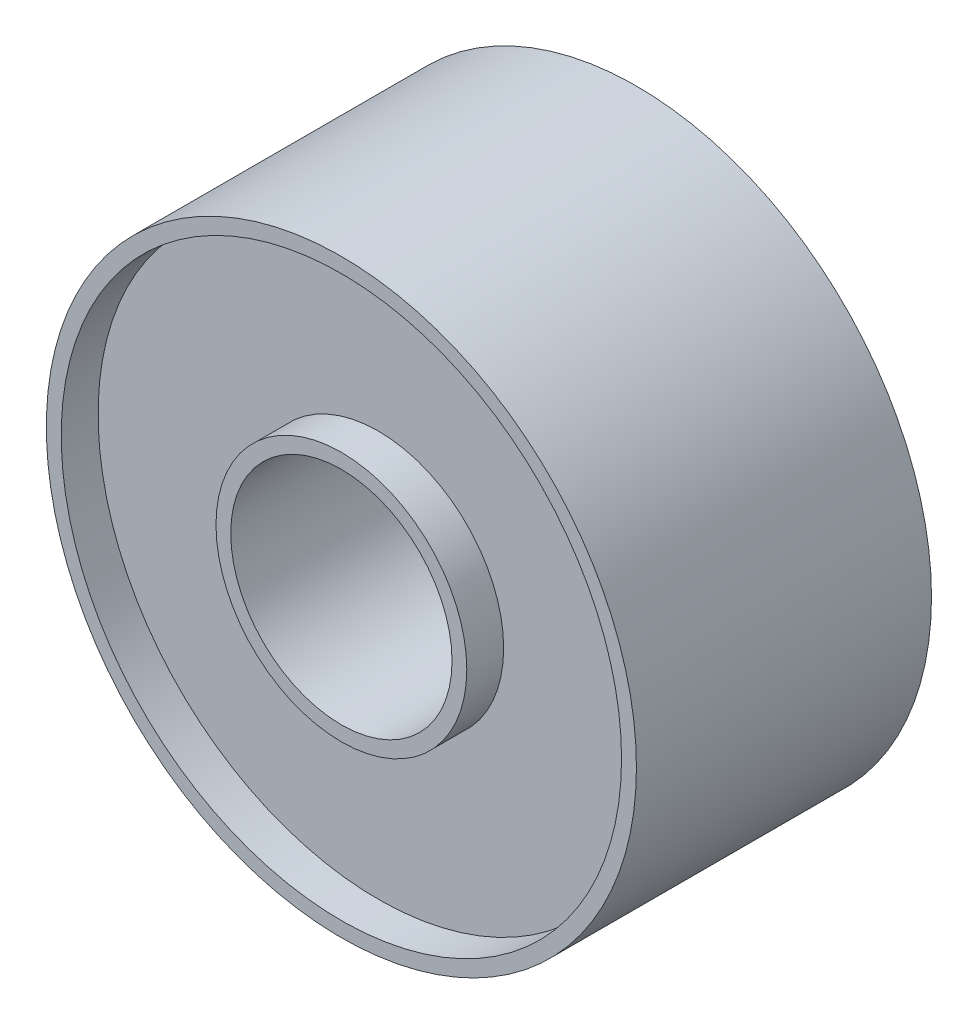
SolidWorks part; units mm, degrees
ref_plane "Front Plane" through (0, 0, 0) normal (0, 0, 1) x (1, 0, 0)
ref_plane "Top Plane" through (0, 0, 0) normal (0, 1, 0) x (1, 0, 0)
ref_plane "Right Plane" through (0, 0, 0) normal (1, 0, 0) x (0, 0, -1)
sketch "Sketch1" plane through (0, 0, 0) normal (0, 0, 1) x (1, 0, 0)
  circle A0 centre (0, 0) radius 4
  circle A1 centre (0, 0) radius 1.5
extrude "Boss-Extrude1" add sketch "Sketch1" along normal blind 4
sketch "Sketch2" plane through (0, 0, 4) normal (0, 0, 1) x (1, 0, 0)
  circle A0 centre (0, 0) radius 3.7982
  circle A1 centre (0, 0) radius 1.7
extrude "Cut-Extrude2" cut sketch "Sketch2" against normal blind 0.5
sketch "Sketch3" plane through (0, 0, 0) normal (0, 0, -1) x (-1, 0, 0)
  circle A0 centre (0, 0) radius 3.7982
  circle A1 centre (0, 0) radius 1.7
extrude "Cut-Extrude3" cut sketch "Sketch3" against normal blind 0.5
